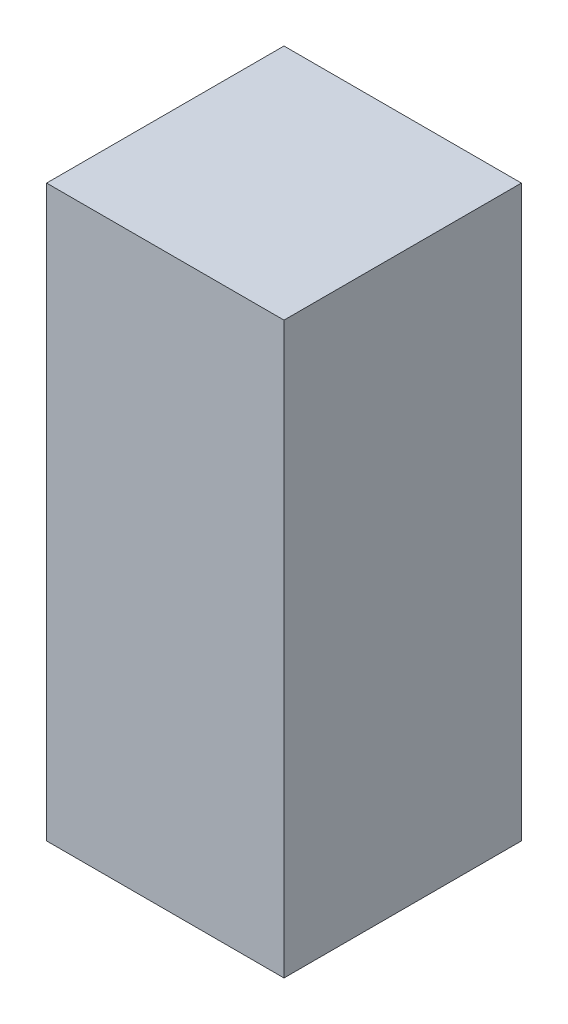
SolidWorks part; units mm, degrees
material "Balsa"
ref_plane "Alzado" through (0, 0, 0) normal (0, 0, 1) x (1, 0, 0)
ref_plane "Planta" through (0, 0, 0) normal (0, 1, 0) x (1, 0, 0)
ref_plane "Vista lateral" through (0, 0, 0) normal (1, 0, 0) x (0, 0, -1)
sketch "Croquis1" plane through (0, 0, 0) normal (0, 1, 0) x (1, 0, 0)
  line L1 (-2.5, -2.5) -> (2.5, -2.5)
  line L2 (-2.5, -2.5) -> (-2.5, 2.5)
  line L3 (-2.5, 2.5) -> (2.5, 2.5)
  line L4 (2.5, -2.5) -> (2.5, 2.5)
  line L5 (-2.5, -2.5) -> (2.5, 2.5) construction
  line L6 (-2.5, 2.5) -> (2.5, -2.5) construction
  point P0 (0, 0)
  dimension "D1" = 5
  dimension "D2" = 5
extrude "Saliente-Extruir1" add sketch "Croquis1" along normal mid plane 12
